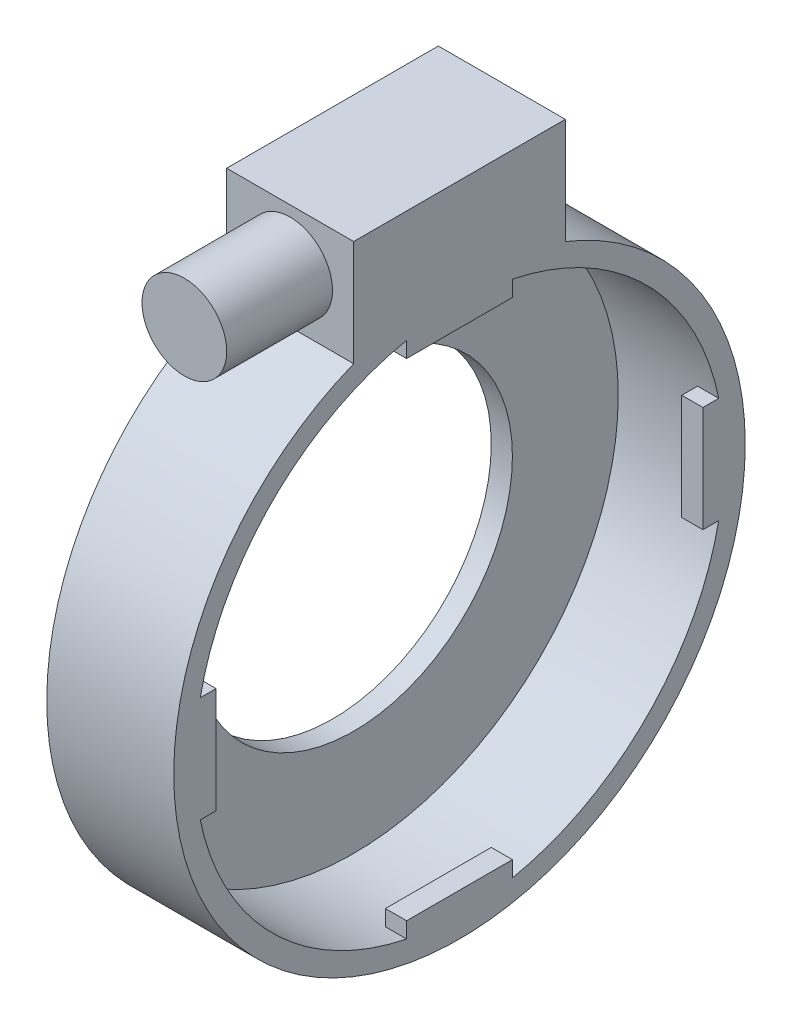
SolidWorks part; units mm, degrees
material "ABS"
ref_plane "Front Plane" through (0, 0, 0) normal (0, 0, 1) x (1, 0, 0)
ref_plane "Top Plane" through (0, 0, 0) normal (0, 1, 0) x (1, 0, 0)
ref_plane "Right Plane" through (0, 0, 0) normal (1, 0, 0) x (0, 0, -1)
sketch "Sketch1" plane through (0, 0, 0) normal (1, 0, 0) x (0, 0, -1)
  line L2 (-10, 25.0799) -> (-10, 35.0799)
  line L3 (-10, 35.0799) -> (10, 35.0799)
  line L4 (10, 25.0799) -> (10, 35.0799)
  arc A0 (-10, 25.0799) -> (10, 25.0799) centre (0, 0) ccw
  circle A1 centre (0, 0) radius 15
  point P1 (0, 35.0799)
  dimension "D1" = 54
  dimension "D4" = 30
  dimension "D2" = 10
  dimension "D3" = 20
extrude "Boss-Extrude1" add sketch "Sketch1" along normal blind 12
sketch "Sketch2" plane through (12, 0, 0) normal (1, 0, 0) x (0, 0, -1)
  circle A0 centre (0, 0) radius 25
  dimension "D1" = 50
extrude "Cut-Extrude1" cut sketch "Sketch2" against normal blind 10
sketch "Sketch3" plane through (0, 0, 10) normal (0, 0, 1) x (1, 0, 0)
  line L0 (12, 35.0799) -> (0, 35.0799) construction
  line L1 (12, 35.0799) -> (12, 25.0799) construction
  circle A0 centre (6, 30.0799) radius 4
  point P6 (6, 35.0799)
  point P9 (12, 30.0799)
  dimension "D1" = 8
extrude "Boss-Extrude2" add sketch "Sketch3" along normal blind 10
sketch "Sketch4" plane through (12, 0, 0) normal (1, 0, 0) x (0, 0, -1)
  line L0 (-5, 24.4949) -> (-5, 23)
  line L5 (-5, 23) -> (5, 23)
  line L6 (5, 23) -> (5, 24.4949)
  line L7 (24.4949, 5) -> (23, 5)
  line L8 (23, 5) -> (23, -5)
  line L9 (23, -5) -> (24.4949, -5)
  line L10 (5, -24.4949) -> (5, -23)
  line L11 (5, -23) -> (-5, -23)
  line L12 (-5, -23) -> (-5, -24.4949)
  line L13 (-24.4949, -5) -> (-23, -5)
  line L14 (-23, -5) -> (-23, 5)
  line L15 (-23, 5) -> (-24.4949, 5)
  circle A3 centre (0, 0) radius 25 construction
  circle A5 centre (0, 0) radius 25
  circle A6 centre (0, 0) radius 25 construction
  point P4 (0, 23)
  point P24 (0, 0)
  circle M5 centre (0, 0) radius 25
  dimension "D1" = 23
  dimension "D2" = 10
  dimension "D3" = 4
extrude "Boss-Extrude3" add sketch "Sketch4" against normal blind 2 contours L14 L15 L13 M5 | L5 L6 L0 M5 | L8 L9 L7 M5 | L11 L12 L10 M5
